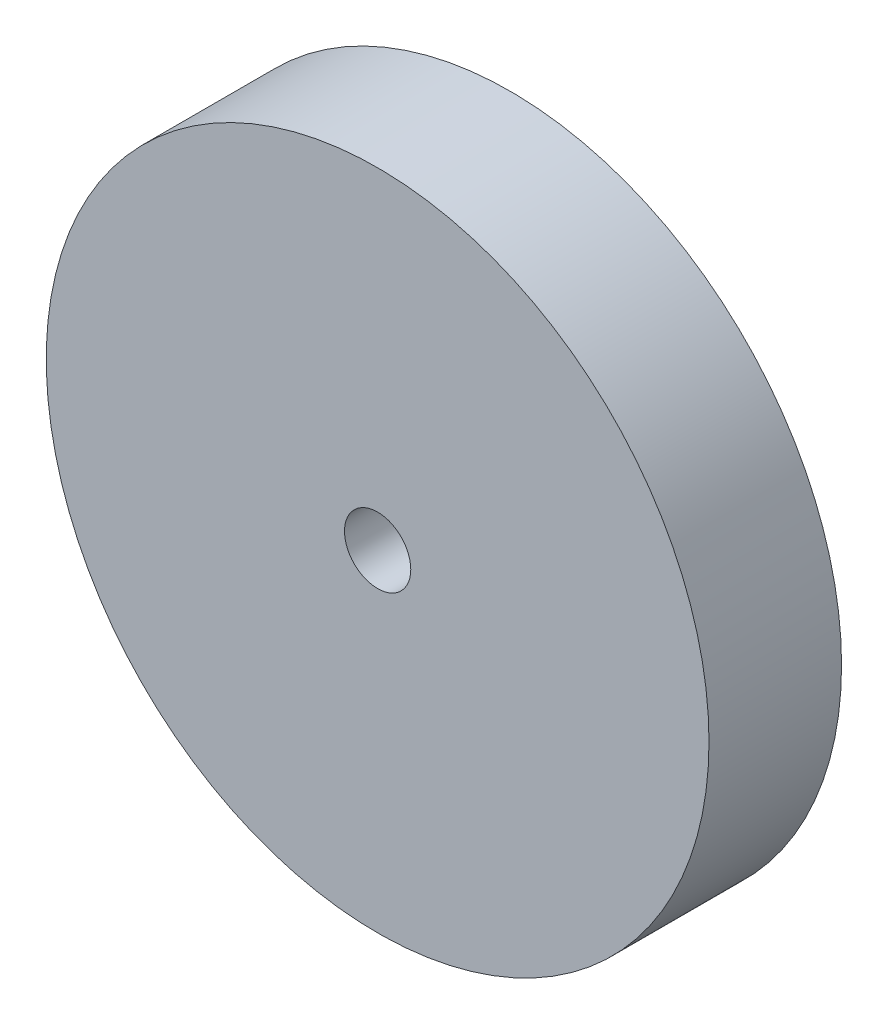
SolidWorks part; units mm, degrees
ref_plane "Front Plane" through (0, 0, 0) normal (0, 0, 1) x (1, 0, 0)
ref_plane "Top Plane" through (0, 0, 0) normal (0, 1, 0) x (1, 0, 0)
ref_plane "Right Plane" through (0, 0, 0) normal (1, 0, 0) x (0, 0, -1)
sketch "Sketch1" plane through (0, 0, 0) normal (0, 0, 1) x (1, 0, 0)
  circle A0 centre (11.5, -184.6746) radius 5
  circle A2 centre (11.5, -184.6746) radius 50
  dimension "D1" = 100
  dimension "D2" = 10
extrude "Boss-Extrude1" add sketch "Sketch1" against normal blind 20
